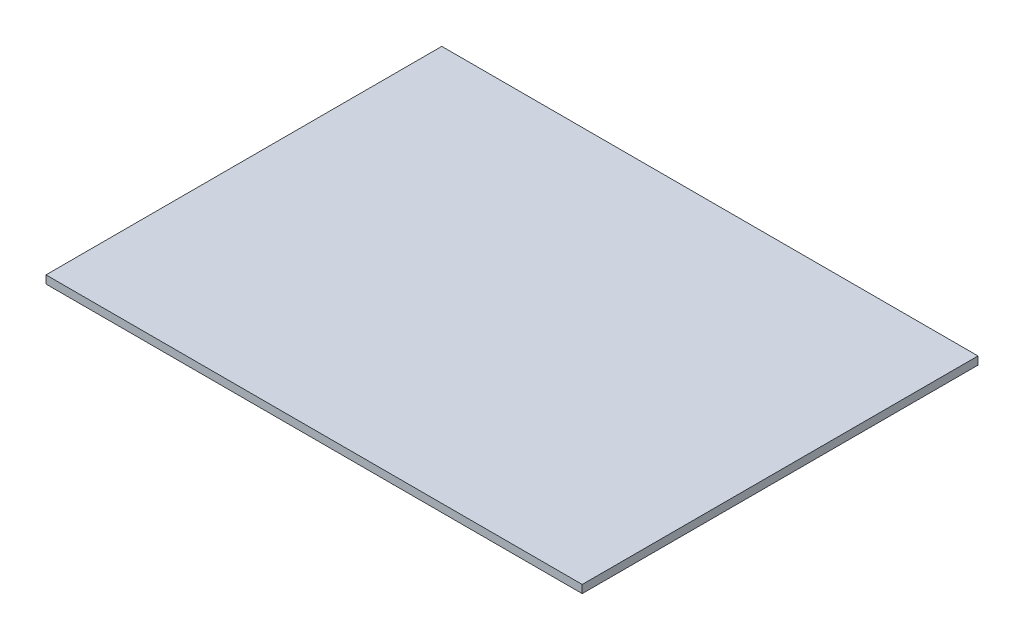
SolidWorks part; units mm, degrees
ref_plane "Front Plane" through (0, 0, 0) normal (0, 0, 1) x (1, 0, 0)
ref_plane "Top Plane" through (0, 0, 0) normal (0, 1, 0) x (1, 0, 0)
ref_plane "Right Plane" through (0, 0, 0) normal (1, 0, 0) x (0, 0, -1)
sketch "Sketch1" plane through (0, 0, 0) normal (0, 1, 0) x (1, 0, 0)
  line L0 (-148, 124) -> (-166.9743, 124)
  line L1 (-148, -124) -> (148, -124)
  line L2 (-148, -124) -> (-148, 124) construction
  line L3 (-148, 124) -> (148, 124)
  line L4 (148, -124) -> (148, 124) construction
  line L5 (-148, -124) -> (148, 124) construction
  line L6 (-148, 124) -> (148, -124) construction
  line L7 (-166.9743, 124) -> (-166.9743, -124)
  line L8 (-166.9743, -124) -> (-148, -124)
  line L9 (148, -124) -> (169.0257, -124)
  line L10 (169.0257, -124) -> (169.0257, 124)
  line L11 (169.0257, 124) -> (148, 124)
  point P0 (0, 0)
  dimension "D1" = 296
  dimension "D2" = 248
  dimension "D3" = 336
extrude "Boss-Extrude1" add sketch "Sketch1" along normal blind 5
